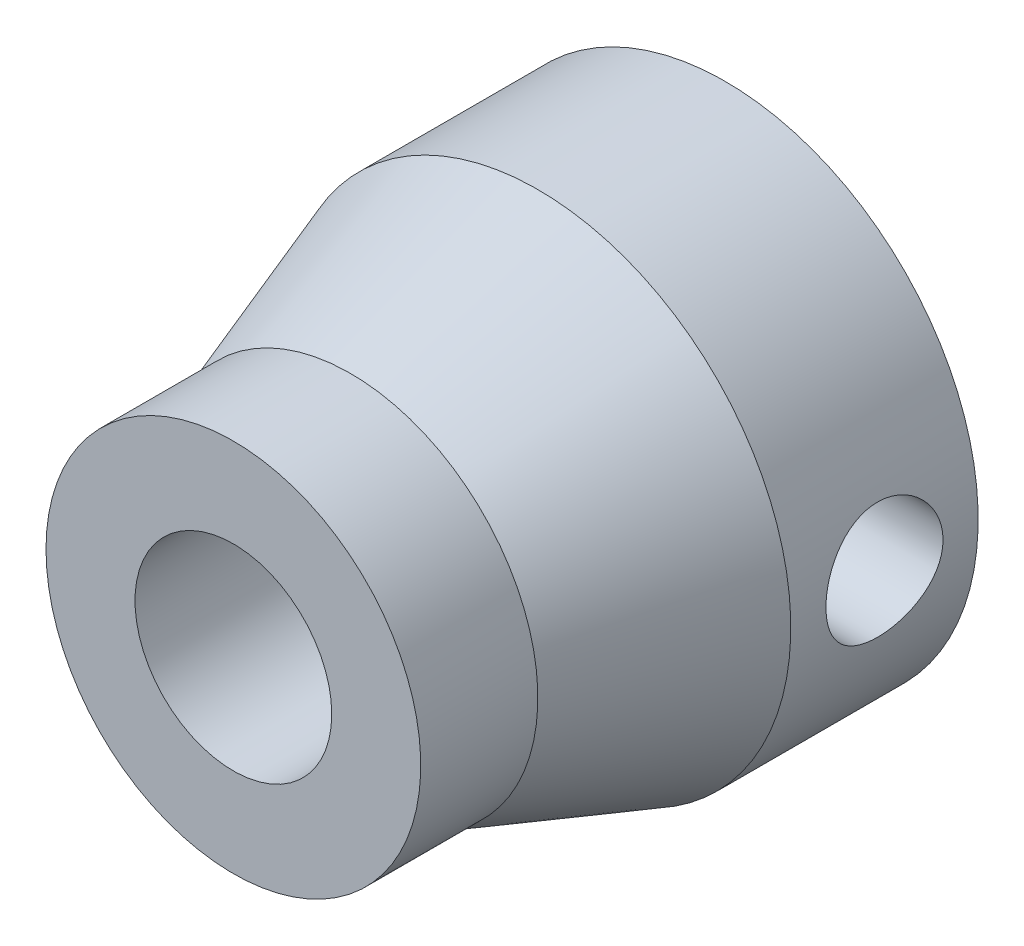
SolidWorks part; units mm, degrees
ref_plane "Top" through (0, 0, 0) normal (0, 0, 1) x (1, 0, 0)
ref_plane "Front" through (0, 0, 0) normal (0, 1, 0) x (1, 0, 0)
ref_plane "Right" through (0, 0, 0) normal (1, 0, 0) x (0, 0, -1)
ref_plane "Base Tangent Plane" through (5.4, 0, 0) normal (1, 0, 0) x (0, 0, -1)
sketch "Body Sketch" plane through (0, 0, 0) normal (0, 1, 0) x (-1, 0, 0)
  line L1 (1, 10.5) -> (4, 10.5)
  line L2 (4, 10.5) -> (4, 8)
  line L3 (4, 8) -> (5.4, 4)
  line L4 (5.4, 4) -> (5.4, 0)
  line L5 (5.4, 0) -> (2.5, 0)
  line L8 (0, 0) -> (0, 10.5) construction
  line L9 (1, 10.5) -> (1, 5)
  line L10 (1, 5) -> (2.5, 5)
  line L11 (2.5, 5) -> (2.5, 0)
  dimension "D1" = 4
  dimension "D6" = 2.5
  dimension "D2" = 10.5
  dimension "D4" = 5.4
  dimension "D3" = 4
  dimension "D5" = 2.5
  dimension "D7" = 1
  dimension "D8" = 5
revolve "Body Revolve" add sketch "Body Sketch" angle 360 about L8
hole_wizard "Connector M5x0.8 Tapped Hole" positions "Connector Position Sketch" profile "Sketch5" tap size "M5x0.8" standard "ANSI Metric" end condition through all
sketch "Connector Position Sketch" plane through (0, 0, 10.5) normal (0, 0, 1) x (1, 0, 0)
  point P0 (0, 0)
cosmetic thread "Connector Hole Thread" parameters "D2"=5
sketch "Sketch5" plane through (0, 0, 10.5) normal (1, 0, 0) x (0, -1, 0)
  line L0 (0, 0) -> (0, 10.5)
  line L1 (0, 10.5) -> (2.1, 10.5)
  line L2 (2.1, 10.5) -> (2.1, 0)
  line L5 (2.1, 0) -> (0, 0)
  line L11 (0, -6.35) -> (0, 107.95) construction
  dimension "Thru Tap Drill Dia." = 4.2
  dimension "Thru Tap Drill Depth" = 10.5
hole_wizard "Set Screw 1 M3x0.5 Tapped Hole" positions "Set Screw Position Sketch" profile "Set Screw Profile Sketch" tap size "M3x0.5" standard "ANSI Metric"
sketch3d "Set Screw Position Sketch"
  point P0 (5.4, 0, 2)
  dimension "D1" = 2
sketch "Set Screw Profile Sketch" plane through (5.4, 0, 2) normal (0, 1, 0) x (0, 0, -1)
  line L0 (0, 0) -> (0, 2.9)
  line L1 (0, 2.9) -> (1.25, 2.9)
  line L2 (1.25, 2.9) -> (1.25, 0)
  line L5 (1.25, 0) -> (0, 0)
  line L11 (0, -6.35) -> (0, 107.95) construction
  dimension "Thru Tap Drill Dia." = 2.5
  dimension "Thru Tap Drill Depth" = 2.9
cosmetic thread "Set Screw 1 Hole Thread" parameters "D2"=3
equation "\"Base Diameter\"= 10.8"
equation "\"D4@Body Sketch\"=\"Base Diameter\"/2"
equation "\"D1@Base Tangent Plane\"=\"Base Diameter\"/2"
